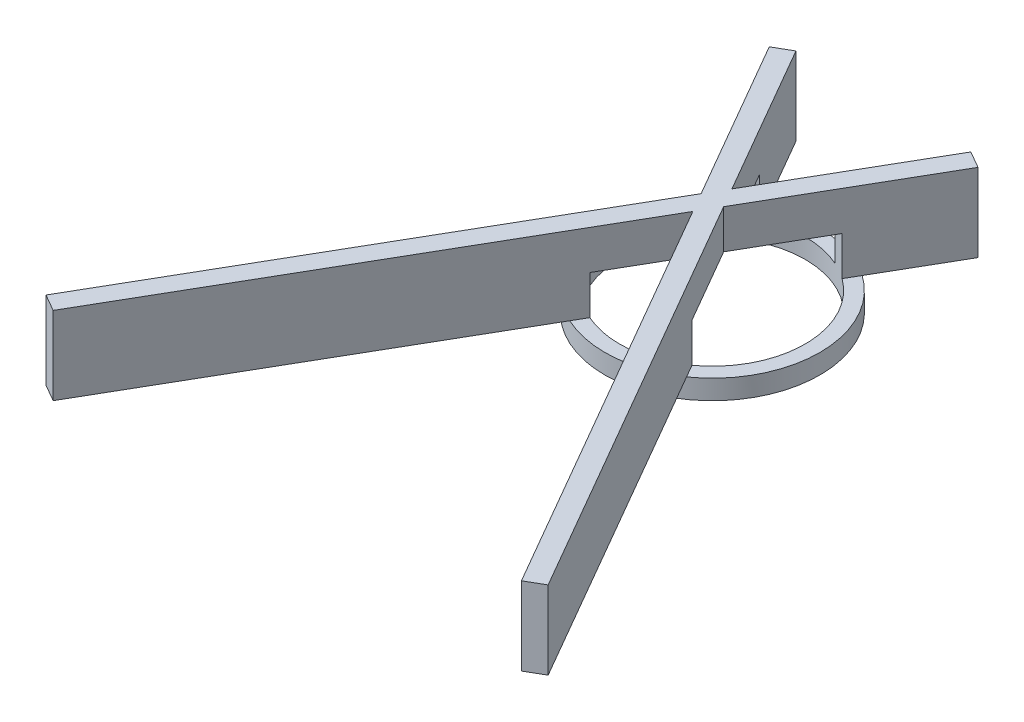
SolidWorks part; units mm, degrees
ref_plane "Front Plane" through (0, 0, 0) normal (0, 0, 1) x (1, 0, 0)
ref_plane "Top Plane" through (0, 0, 0) normal (0, 1, 0) x (1, 0, 0)
ref_plane "Right Plane" through (0, 0, 0) normal (1, 0, 0) x (0, 0, -1)
sketch "Sketch1" plane through (0, 2, 0) normal (0, 1, 0) x (1, 0, 0)
  circle A0 centre (0, 0) radius 11
  arc A1 (11.4991, 0.1463) -> (11.0418, 3.2139) centre (0, 0) ccw construction
  circle A2 centre (0, 0) radius 9.5
  dimension "D1" = 0.5
  dimension "D2" = 1.5
extrude "Boss-Extrude1" add sketch "Sketch1" against normal blind 2
sketch "Sketch2" plane through (0, 2, 0) normal (0, 1, 0) x (1, 0, 0)
  line L0 (-24.8261, -43) -> (9.815, 17)
  line L1 (-9.815, 17) -> (9.815, 17) construction
  line L2 (-9.815, 17) -> (24.8261, -43)
  line L3 (24.8261, -43) -> (-24.8261, -43) construction
  line L4 (0, 17) -> (0, -43) construction
  circle A1 centre (0, 0) radius 17 construction
  dimension "D1" = 60
  dimension "D2" = 60
extrude "Extrude-Thin1" add sketch "Sketch2" along normal blind 8 thin thin type mid plane wall 2
sketch "Sketch3" plane through (0, 0, 0) normal (0, -1, 0) x (1, 0, 0)
  circle A0 centre (0, 0) radius 9.5
  circle A1 centre (0, 0) radius 9.5 construction
extrude "Cut-Extrude1" cut sketch "Sketch3" against normal offset from surface (6 mm away) 4 up to face at (0, 10, 8.6667)
